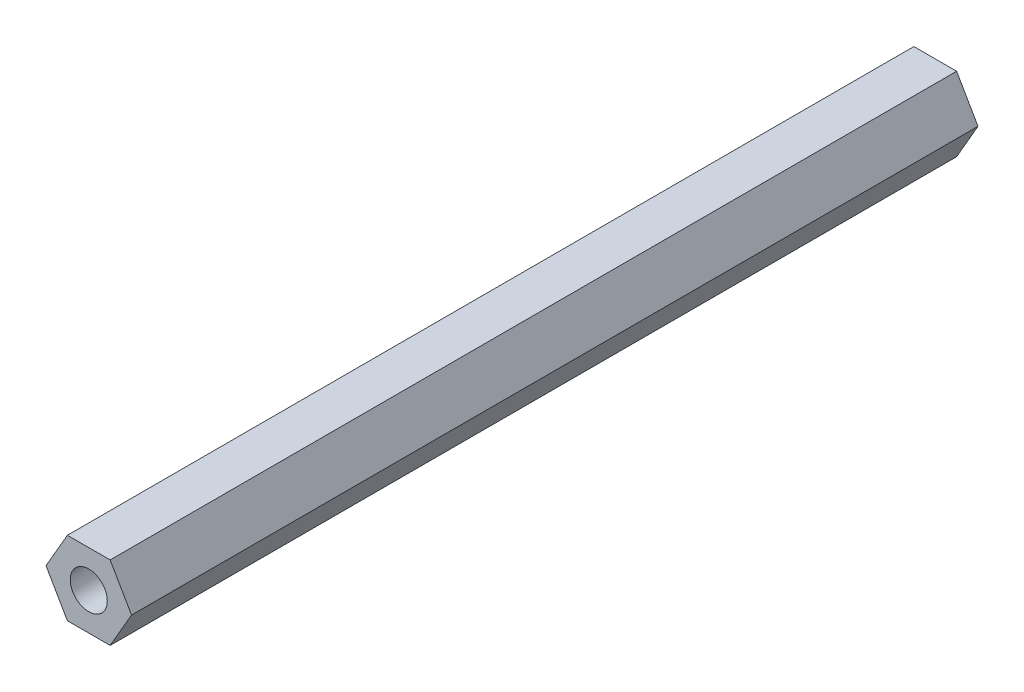
SolidWorks part; units mm, degrees
ref_plane "Front" through (0, 0, 0) normal (0, 0, 1) x (1, 0, 0)
ref_plane "Top" through (0, 0, 0) normal (0, 1, 0) x (1, 0, 0)
ref_plane "Right" through (0, 0, 0) normal (1, 0, 0) x (0, 0, -1)
sketch "Sketch1" plane through (0, 0, 0) normal (0, 0, 1) x (1, 0, 0)
  line L1 (4.0415, 0) -> (2.0207, 3.5)
  line L2 (2.0207, 3.5) -> (-2.0207, 3.5)
  line L3 (-2.0207, 3.5) -> (-4.0415, 0)
  line L4 (-4.0415, 0) -> (-2.0207, -3.5)
  line L5 (-2.0207, -3.5) -> (2.0207, -3.5)
  line L6 (2.0207, -3.5) -> (4.0415, 0)
  circle A0 centre (0, 0) radius 3.5 construction
  dimension "D1" = 7
extrude "f" add sketch "Sketch1" along normal blind 80
sketch "Sketch2" plane through (0, 0, 80) normal (0, 0, 1) x (1, 0, 0)
  circle A0 centre (0, 0) radius 1.75
  dimension "D1" = 1.75
extrude "Cut-Extrude1" cut sketch "Sketch2" against normal blind 6.1
sketch "Sketch3" plane through (0, 0, 0) normal (0, 0, -1) x (-1, 0, 0)
  circle A0 centre (0, 0) radius 1.75
  dimension "D1" = 1.75
extrude "Cut-Extrude2" cut sketch "Sketch3" against normal blind 6.1
